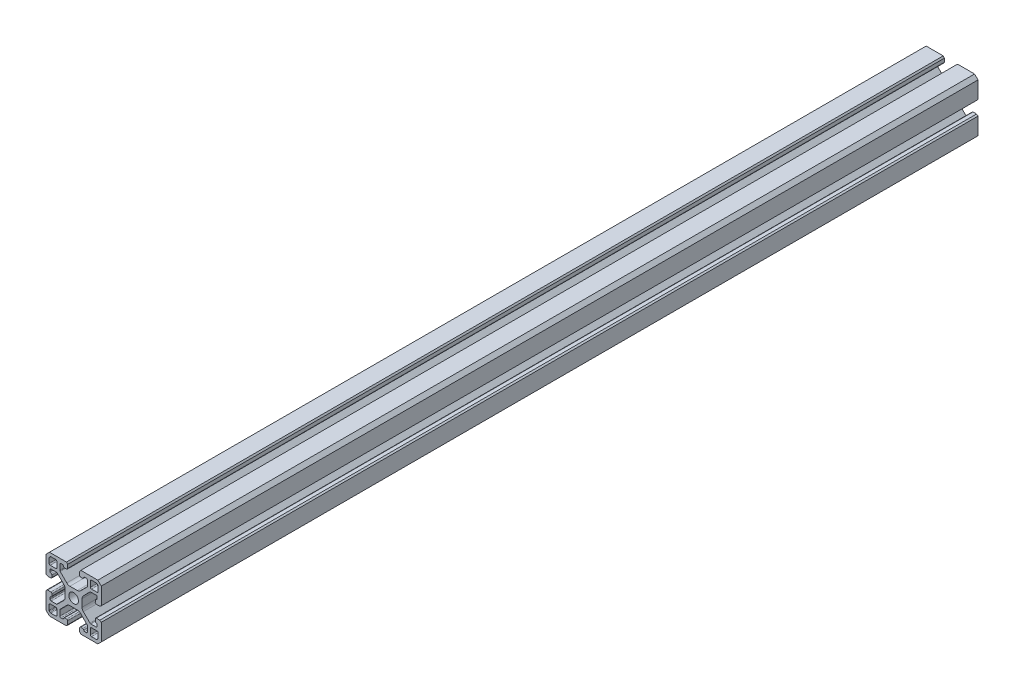
SolidWorks part; units mm, degrees
material "6063-T6"
ref_plane "Front Plane" through (0, 0, 0) normal (0, 0, 1) x (1, 0, 0)
ref_plane "Top Plane" through (0, 0, 0) normal (0, 1, 0) x (1, 0, 0)
ref_plane "Right Plane" through (0, 0, 0) normal (1, 0, 0) x (0, 0, -1)
sketch "Sketch1" plane through (0, 0, 0) normal (0, 0, 1) x (-1, 0, 0)
  line L0 (19.05, 0) -> (-19.05, 0) construction
  line L1 (0, -19.05) -> (0, 19.05) construction
  line L2 (-19.05, 4.9276) -> (-19.05, 16.6878)
  line L3 (-18.044, 4.1656) -> (-19.05, 4.9276)
  line L4 (-15.6692, 4.1656) -> (-18.044, 4.1656)
  line L5 (-14.9297, 6.2238) -> (-14.9074, 4.9409)
  line L6 (-16.256, 8.763) -> (-16.256, 7.7216)
  line L7 (-16.256, -7.7216) -> (-16.256, -8.763)
  line L8 (-14.9074, -4.9409) -> (-14.9297, -6.2238)
  line L9 (-18.044, -4.1656) -> (-15.6692, -4.1656)
  line L10 (-19.05, -4.9276) -> (-18.044, -4.1656)
  line L11 (-19.05, -16.6878) -> (-19.05, -4.9276)
  line L26 (-16.8656, 12.319) -> (-16.8656, 15.6829)
  line L27 (-16.6424, 16.2217) -> (-16.2217, 16.6424)
  line L28 (-15.6829, 16.8656) -> (-12.319, 16.8656)
  line L29 (-11.557, 16.1036) -> (-11.557, 12.319)
  line L30 (-12.319, 11.557) -> (-16.1036, 11.557)
  line L31 (-6.7001, -4.7245) -> (-11.2775, -9.3018)
  line L32 (-11.8163, -9.525) -> (-15.494, -9.525)
  line L34 (-15.494, 9.525) -> (-11.8163, 9.525)
  line L35 (-11.2775, 9.3018) -> (-6.7001, 4.7245)
  line L36 (-5.8074, 2.5692) -> (-5.8074, -2.5692)
  line L37 (-16.1036, -11.557) -> (-12.319, -11.557)
  line L38 (-11.557, -12.319) -> (-11.557, -16.1036)
  line L39 (-12.319, -16.8656) -> (-15.6829, -16.8656)
  line L40 (-16.2217, -16.6424) -> (-16.6424, -16.2217)
  line L41 (-16.8656, -15.6829) -> (-16.8656, -12.319)
  line L42 (15.6829, -16.8656) -> (12.319, -16.8656)
  line L43 (11.557, -16.1036) -> (11.557, -12.319)
  line L44 (12.319, -11.557) -> (16.1036, -11.557)
  line L45 (16.8656, -12.319) -> (16.8656, -15.6829)
  line L46 (16.6424, -16.2217) -> (16.2217, -16.6424)
  line L47 (11.557, 12.319) -> (11.557, 16.1036)
  line L48 (12.319, 16.8656) -> (15.6829, 16.8656)
  line L49 (16.2217, 16.6424) -> (16.6424, 16.2217)
  line L100 (5.8074, -2.5692) -> (5.8074, 2.5692)
  line L101 (6.7001, 4.7245) -> (11.2775, 9.3018)
  line L102 (11.8163, 9.525) -> (15.494, 9.525)
  line L103 (16.256, 8.763) -> (16.256, 7.7216)
  line L104 (14.9297, 6.2238) -> (14.9074, 4.9409)
  line L105 (15.6692, 4.1656) -> (18.044, 4.1656)
  line L106 (18.044, 4.1656) -> (19.05, 4.9276)
  line L107 (19.05, 4.9276) -> (19.05, 16.6878)
  line L108 (19.05, 16.6878) -> (16.6878, 19.05)
  line L109 (16.6878, 19.05) -> (4.9276, 19.05)
  line L110 (4.9276, 19.05) -> (4.1656, 18.044)
  line L111 (4.1656, 18.044) -> (4.1656, 15.6692)
  line L112 (4.9409, 14.9074) -> (6.2238, 14.9297)
  line L113 (7.7216, 16.256) -> (8.763, 16.256)
  line L114 (9.525, 15.494) -> (9.525, 11.8163)
  line L115 (9.3018, 11.2775) -> (4.7245, 6.7001)
  line L116 (2.5692, 5.8074) -> (-2.5692, 5.8074)
  line L117 (-4.7245, 6.7001) -> (-9.3018, 11.2775)
  line L118 (-9.525, 11.8163) -> (-9.525, 15.494)
  line L119 (-8.763, 16.256) -> (-7.7216, 16.256)
  line L120 (-6.2238, 14.9297) -> (-4.9409, 14.9074)
  line L121 (-4.1656, 15.6692) -> (-4.1656, 18.044)
  line L122 (-4.1656, 18.044) -> (-4.9276, 19.05)
  line L123 (-4.9276, 19.05) -> (-16.6878, 19.05)
  line L124 (-16.6878, 19.05) -> (-19.05, 16.6878)
  line L126 (-19.05, -16.6878) -> (-16.6878, -19.05)
  line L127 (-16.6878, -19.05) -> (-4.9276, -19.05)
  line L128 (-4.9276, -19.05) -> (-4.1656, -18.044)
  line L129 (-4.1656, -18.044) -> (-4.1656, -15.6692)
  line L130 (-4.9409, -14.9074) -> (-6.2238, -14.9297)
  line L131 (-7.7216, -16.256) -> (-8.763, -16.256)
  line L132 (-9.525, -15.494) -> (-9.525, -11.8163)
  line L133 (-9.3018, -11.2775) -> (-4.7245, -6.7001)
  line L134 (-2.5692, -5.8074) -> (2.5692, -5.8074)
  line L135 (4.7245, -6.7001) -> (9.3018, -11.2775)
  line L136 (9.525, -11.8163) -> (9.525, -15.494)
  line L137 (8.763, -16.256) -> (7.7216, -16.256)
  line L138 (6.2238, -14.9297) -> (4.9409, -14.9074)
  line L139 (4.1656, -15.6692) -> (4.1656, -18.044)
  line L140 (4.1656, -18.044) -> (4.9409, -19.05)
  line L141 (4.9409, -19.05) -> (16.6878, -19.05)
  line L142 (16.6878, -19.05) -> (19.05, -16.6878)
  line L143 (19.05, -16.6878) -> (19.05, -4.9276)
  line L144 (19.05, -4.9276) -> (18.044, -4.1656)
  line L145 (18.044, -4.1656) -> (15.6692, -4.1656)
  line L146 (14.9074, -4.9409) -> (14.9297, -6.2238)
  line L147 (16.256, -7.7216) -> (16.256, -8.763)
  line L148 (15.494, -9.525) -> (11.8163, -9.525)
  line L149 (11.2775, -9.3018) -> (6.7001, -4.7245)
  line L150 (16.8656, 15.6829) -> (16.8656, 12.319)
  line L151 (16.1036, 11.557) -> (12.319, 11.557)
  arc A0 (-16.256, 8.763) -> (-15.494, 9.525) centre (-15.494, 8.763) cw
  arc A1 (-14.9074, 4.9409) -> (-15.6692, 4.1656) centre (-15.6692, 4.9276) cw
  arc A2 (-15.5928, 6.966) -> (-14.9297, 6.2238) centre (-15.6916, 6.2105) cw
  arc A3 (-15.5928, 6.966) -> (-16.256, 7.7216) centre (-15.494, 7.7216) cw
  arc A4 (-15.494, -9.525) -> (-16.256, -8.763) centre (-15.494, -8.763) cw
  arc A5 (-16.256, -7.7216) -> (-15.5928, -6.966) centre (-15.494, -7.7216) cw
  arc A6 (-14.9297, -6.2238) -> (-15.5928, -6.966) centre (-15.6916, -6.2105) cw
  arc A7 (-15.6692, -4.1656) -> (-14.9074, -4.9409) centre (-15.6692, -4.9276) cw
  arc A27 (-16.6424, 16.2217) -> (-16.8656, 15.6829) centre (-16.1036, 15.6829) ccw
  arc A28 (-15.6829, 16.8656) -> (-16.2217, 16.6424) centre (-15.6829, 16.1036) ccw
  arc A29 (-11.557, 16.1036) -> (-12.319, 16.8656) centre (-12.319, 16.1036) ccw
  arc A30 (-12.319, 11.557) -> (-11.557, 12.319) centre (-12.319, 12.319) ccw
  arc A31 (-16.8656, 12.319) -> (-16.1036, 11.557) centre (-16.1036, 12.319) ccw
  arc A32 (-11.8163, -9.525) -> (-11.2775, -9.3018) centre (-11.8163, -8.763) ccw
  arc A35 (-11.2775, 9.3018) -> (-11.8163, 9.525) centre (-11.8163, 8.763) ccw
  arc A72 (5.8074, -2.5692) -> (6.7001, -4.7245) centre (8.8554, -2.5692) ccw
  arc A73 (6.7001, 4.7245) -> (5.8074, 2.5692) centre (8.8554, 2.5692) ccw
  arc A74 (11.8163, 9.525) -> (11.2775, 9.3018) centre (11.8163, 8.763) ccw
  arc A75 (16.256, 8.763) -> (15.494, 9.525) centre (15.494, 8.763) ccw
  arc A76 (15.5928, 6.966) -> (16.256, 7.7216) centre (15.494, 7.7216) ccw
  arc A77 (15.5928, 6.966) -> (14.9297, 6.2238) centre (15.6916, 6.2105) ccw
  arc A78 (14.9074, 4.9409) -> (15.6692, 4.1656) centre (15.6692, 4.9276) ccw
  arc A79 (4.1656, 15.6692) -> (4.9409, 14.9074) centre (4.9276, 15.6692) ccw
  arc A80 (6.2238, 14.9297) -> (6.966, 15.5928) centre (6.2105, 15.6916) ccw
  arc A81 (7.7216, 16.256) -> (6.966, 15.5928) centre (7.7216, 15.494) ccw
  arc A82 (9.525, 15.494) -> (8.763, 16.256) centre (8.763, 15.494) ccw
  arc A83 (9.3018, 11.2775) -> (9.525, 11.8163) centre (8.763, 11.8163) ccw
  arc A84 (2.5692, 5.8074) -> (4.7245, 6.7001) centre (2.5692, 8.8554) ccw
  arc A85 (-4.7245, 6.7001) -> (-2.5692, 5.8074) centre (-2.5692, 8.8554) ccw
  arc A86 (-9.525, 11.8163) -> (-9.3018, 11.2775) centre (-8.763, 11.8163) ccw
  arc A87 (-8.763, 16.256) -> (-9.525, 15.494) centre (-8.763, 15.494) ccw
  arc A88 (-6.966, 15.5928) -> (-7.7216, 16.256) centre (-7.7216, 15.494) ccw
  arc A89 (-6.966, 15.5928) -> (-6.2238, 14.9297) centre (-6.2105, 15.6916) ccw
  arc A90 (-4.9409, 14.9074) -> (-4.1656, 15.6692) centre (-4.9276, 15.6692) ccw
  arc A91 (-4.1656, -15.6692) -> (-4.9409, -14.9074) centre (-4.9276, -15.6692) ccw
  arc A92 (-6.2238, -14.9297) -> (-6.966, -15.5928) centre (-6.2105, -15.6916) ccw
  arc A93 (-7.7216, -16.256) -> (-6.966, -15.5928) centre (-7.7216, -15.494) ccw
  arc A94 (-9.525, -15.494) -> (-8.763, -16.256) centre (-8.763, -15.494) ccw
  arc A95 (-9.3018, -11.2775) -> (-9.525, -11.8163) centre (-8.763, -11.8163) ccw
  arc A96 (-2.5692, -5.8074) -> (-4.7245, -6.7001) centre (-2.5692, -8.8554) ccw
  arc A97 (4.7245, -6.7001) -> (2.5692, -5.8074) centre (2.5692, -8.8554) ccw
  arc A98 (9.525, -11.8163) -> (9.3018, -11.2775) centre (8.763, -11.8163) ccw
  arc A99 (8.763, -16.256) -> (9.525, -15.494) centre (8.763, -15.494) ccw
  arc A100 (6.966, -15.5928) -> (7.7216, -16.256) centre (7.7216, -15.494) ccw
  arc A101 (6.966, -15.5928) -> (6.2238, -14.9297) centre (6.2105, -15.6916) ccw
  arc A102 (4.9409, -14.9074) -> (4.1656, -15.6692) centre (4.9276, -15.6692) ccw
  arc A103 (15.6692, -4.1656) -> (14.9074, -4.9409) centre (15.6692, -4.9276) ccw
  arc A104 (14.9297, -6.2238) -> (15.5928, -6.966) centre (15.6916, -6.2105) ccw
  arc A105 (16.256, -7.7216) -> (15.5928, -6.966) centre (15.494, -7.7216) ccw
  arc A106 (15.494, -9.525) -> (16.256, -8.763) centre (15.494, -8.763) ccw
  arc A107 (11.2775, -9.3018) -> (11.8163, -9.525) centre (11.8163, -8.763) ccw
  arc A108 (-5.8074, 2.5692) -> (-6.7001, 4.7245) centre (-8.8554, 2.5692) ccw
  arc A109 (-6.7001, -4.7245) -> (-5.8074, -2.5692) centre (-8.8554, -2.5692) ccw
  arc A110 (-11.557, -12.319) -> (-12.319, -11.557) centre (-12.319, -12.319) ccw
  arc A111 (-12.319, -16.8656) -> (-11.557, -16.1036) centre (-12.319, -16.1036) ccw
  arc A112 (-16.2217, -16.6424) -> (-15.6829, -16.8656) centre (-15.6829, -16.1036) ccw
  arc A113 (-16.8656, -15.6829) -> (-16.6424, -16.2217) centre (-16.1036, -15.6829) ccw
  arc A114 (-16.1036, -11.557) -> (-16.8656, -12.319) centre (-16.1036, -12.319) ccw
  circle A115 centre (0, 0) radius 3.3147
  arc A116 (11.557, -16.1036) -> (12.319, -16.8656) centre (12.319, -16.1036) ccw
  arc A117 (12.319, -11.557) -> (11.557, -12.319) centre (12.319, -12.319) ccw
  arc A118 (16.8656, -12.319) -> (16.1036, -11.557) centre (16.1036, -12.319) ccw
  arc A119 (16.6424, -16.2217) -> (16.8656, -15.6829) centre (16.1036, -15.6829) ccw
  arc A120 (15.6829, -16.8656) -> (16.2217, -16.6424) centre (15.6829, -16.1036) ccw
  arc A121 (12.319, 16.8656) -> (11.557, 16.1036) centre (12.319, 16.1036) ccw
  arc A122 (16.2217, 16.6424) -> (15.6829, 16.8656) centre (15.6829, 16.1036) ccw
  arc A123 (16.8656, 15.6829) -> (16.6424, 16.2217) centre (16.1036, 15.6829) ccw
  arc A124 (16.1036, 11.557) -> (16.8656, 12.319) centre (16.1036, 12.319) ccw
  arc A125 (11.557, 12.319) -> (12.319, 11.557) centre (12.319, 12.319) ccw
  dimension "D1" = 6.6294
  dimension "D2" = 38.1
  dimension "D3" = 38.1
extrude "Boss-Extrude1" add sketch "Sketch1" along normal blind 604.52
